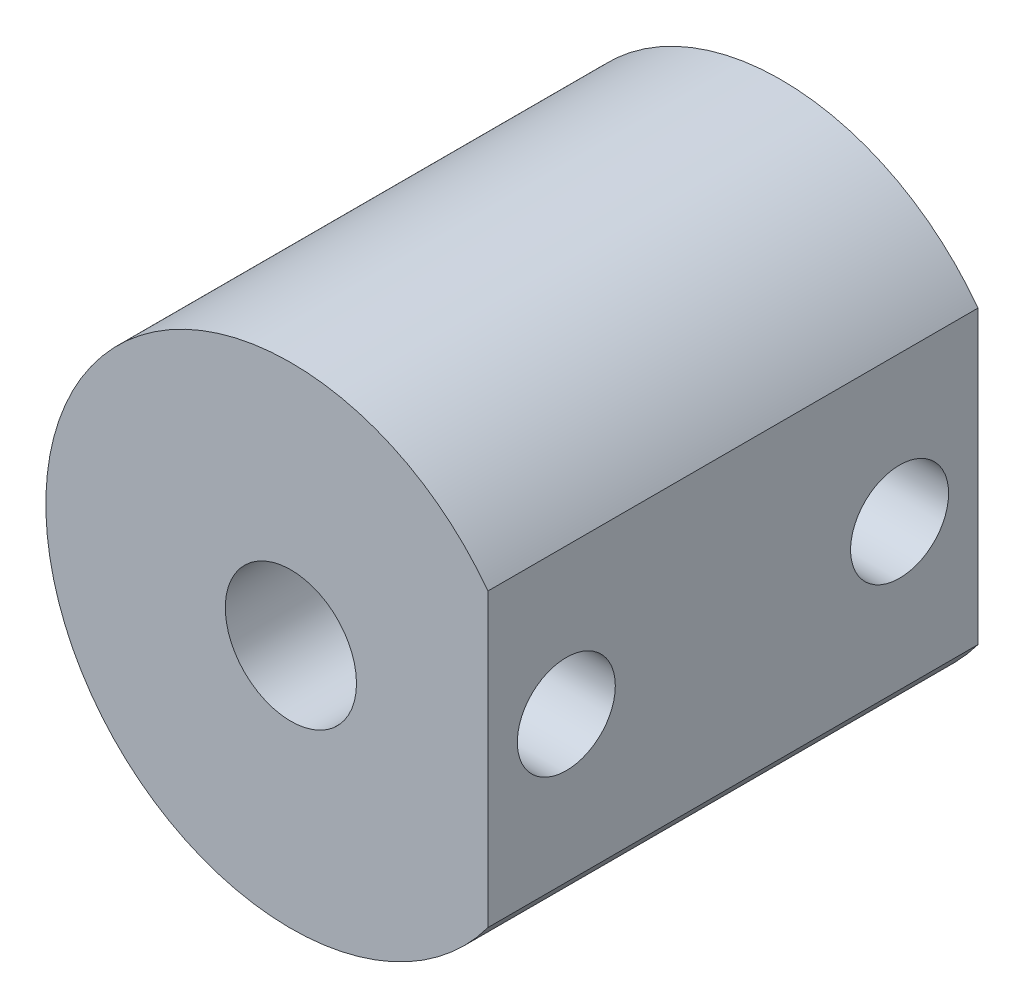
SolidWorks part; units mm, degrees
ref_plane "Front Plane" through (0, 0, 0) normal (0, 0, 1) x (1, 0, 0)
ref_plane "Top Plane" through (0, 0, 0) normal (0, 1, 0) x (1, 0, 0)
ref_plane "Right Plane" through (0, 0, 0) normal (1, 0, 0) x (0, 0, -1)
sketch "Sketch1" plane through (0, 0, 0) normal (0, 0, 1) x (1, 0, 0)
  circle A0 centre (0, 0) radius 6.35
  dimension "D1" = 12.7
extrude "Boss-Extrude1" add sketch "Sketch1" along normal blind 12.7
sketch "Sketch2" plane through (0, 0, 12.7) normal (0, 0, 1) x (1, 0, 0)
  circle A0 centre (0, 0) radius 1.7
  dimension "D1" = 3.4
extrude "Cut-Extrude1" cut sketch "Sketch2" against normal blind 6.35
sketch "Sketch3" plane through (0, 0, 0) normal (0, 0, -1) x (-1, 0, 0)
  line L1 (-2.6462, -1.5365) -> (0.0076, -3.0599)
  line L2 (0.0076, -3.0599) -> (2.6538, -1.5234)
  line L3 (2.6538, -1.5234) -> (2.6462, 1.5365)
  line L4 (2.6462, 1.5365) -> (-0.0076, 3.0599)
  line L5 (-0.0076, 3.0599) -> (-2.6538, 1.5234)
  line L6 (-2.6538, 1.5234) -> (-2.6462, -1.5365)
  circle A0 centre (0, 0) radius 2.65 construction
  dimension "D1" = 5.3
extrude "Cut-Extrude2" cut sketch "Sketch3" against normal blind 6.35
sketch "Sketch4" plane through (0, 0, 0) normal (0, 0, -1) x (-1, 0, 0)
  line L1 (-5.1052, -3.7762) -> (-8.2192, -3.7762)
  line L2 (-5.1052, -3.7762) -> (-5.1052, 4.1225)
  line L3 (-5.1052, 4.1225) -> (-8.2192, 4.1225)
  line L4 (-8.2192, -3.7762) -> (-8.2192, 4.1225)
  circle A0 centre (0, 0) radius 6.35 construction
extrude "Cut-Extrude3" cut sketch "Sketch4" against normal blind 14.224
sketch "Sketch5" plane through (5.1052, 0, 0) normal (1, 0, 0) x (0, 0, -1)
  line L0 (-12.7, 3.7762) -> (-12.7, -3.7762) construction
  line L1 (-12.7, 0) -> (0, 0) construction
  circle A0 centre (-10.668, 0) radius 1.27
  circle A1 centre (-2.032, 0) radius 1.27
  dimension "D1" = 2.54
  dimension "D2" = 2.54
  dimension "D3" = 2.032
  dimension "D4" = 2.032
extrude "Cut-Extrude4" cut sketch "Sketch5" against normal blind 3.81
